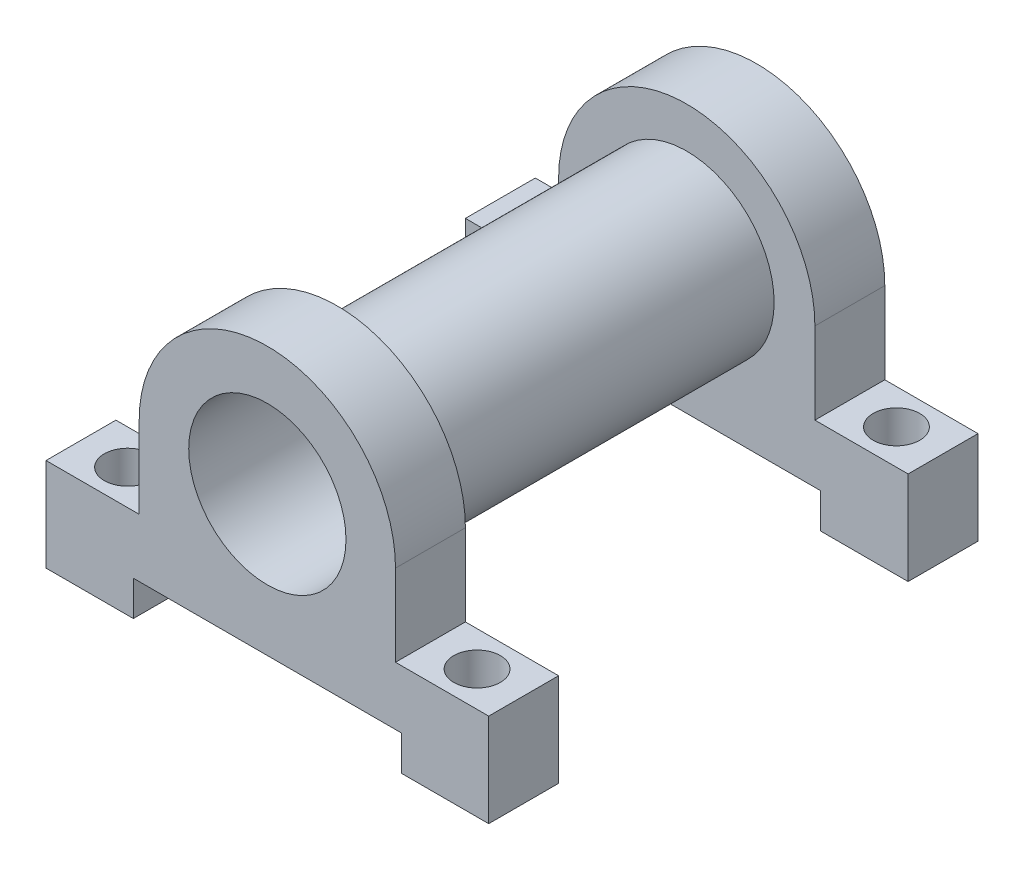
SolidWorks part; units mm, degrees
ref_plane "Front Plane" through (0, 0, 0) normal (0, 0, 1) x (1, 0, 0)
ref_plane "Top Plane" through (0, 0, 0) normal (0, 1, 0) x (1, 0, 0)
ref_plane "Right Plane" through (0, 0, 0) normal (1, 0, 0) x (0, 0, -1)
sketch "Sketch1" plane through (0, 0, 0) normal (0, 0, 1) x (1, 0, 0)
  line L0 (-11, 0) -> (-11, -7)
  line L1 (-11, -15) -> (11, -15)
  line L2 (11, -7) -> (11, 0)
  line L3 (-11, -7) -> (11, -7) construction
  line L4 (-11, -15) -> (-19, -15)
  line L6 (-11, -7) -> (-19, -7)
  line L7 (-19, -15) -> (-19, -7)
  line L8 (11, -15) -> (19, -15)
  line L10 (11, -7) -> (19, -7)
  line L11 (19, -15) -> (19, -7)
  line L12 (-11, 0) -> (11, 0) construction
  line L13 (-11, -7) -> (-11, -15) construction
  line L14 (11, -7) -> (11, -15) construction
  arc A0 (11, 0) -> (-11, 0) centre (0, 0) ccw
  dimension "D1" = 22
  dimension "D2" = 15
  dimension "D3" = 8
  dimension "D4" = 8
extrude "Boss-Extrude1" add sketch "Sketch1" along normal blind 6
sketch "Sketch2" plane through (0, 0, 6) normal (0, 0, 1) x (1, 0, 0)
  circle A0 centre (0, 0) radius 7.5
  dimension "D1" = 15
extrude "Boss-Extrude2" add sketch "Sketch2" along normal blind 30
sketch "Sketch3" plane through (0, 0, 36) normal (0, 0, 1) x (1, 0, 0)
  line L3 (-11, 0) -> (-11, -7)
  line L4 (-19, -15) -> (19, -15)
  line L5 (11, -7) -> (11, 0)
  line L6 (-11, 0) -> (-11, -7)
  line L7 (-19, -15) -> (19, -15)
  line L8 (11, -7) -> (11, 0)
  line L13 (-19, -7) -> (-19, -15)
  line L14 (-19, -7) -> (-19, -15)
  line L15 (19, -15) -> (19, -7)
  line L16 (19, -15) -> (19, -7)
  line L17 (19, -7) -> (11, -7)
  line L18 (19, -7) -> (11, -7)
  line L19 (-11, -7) -> (-19, -7)
  line L20 (-11, -7) -> (-19, -7)
  arc A2 (11, 0) -> (-11, 0) centre (0, 0) ccw
  arc A3 (11, 0) -> (-11, 0) centre (0, 0) ccw
  dimension "D1" = 0
extrude "Boss-Extrude3" add sketch "Sketch3" along normal blind 6
sketch "Sketch4" plane through (0, 0, 42) normal (0, 0, 1) x (1, 0, 0)
  circle A0 centre (0, 0) radius 6.75
  dimension "D1" = 13.5
extrude "Cut-Extrude1" cut sketch "Sketch4" against normal through all
sketch "Sketch5" plane through (0, 0, 0) normal (0, 0, -1) x (-1, 0, 0)
  line L0 (19, -15) -> (-19, -15) construction
  line L1 (-11.5, -15) -> (11.5, -15)
  line L2 (-11.5, -15) -> (-11.5, -12)
  line L3 (-11.5, -12) -> (11.5, -12)
  line L4 (11.5, -15) -> (11.5, -12)
  line L5 (0, -12) -> (0, 0) construction
  dimension "D1" = 23
  dimension "D2" = 3
extrude "Cut-Extrude2" cut sketch "Sketch5" against normal through all and the other way through all
sketch "Sketch6" plane through (0, -7, 0) normal (0, 1, 0) x (1, 0, 0)
  line L0 (-15, -3) -> (15, -3) construction
  line L1 (19, -42) -> (11, -42) construction
  line L3 (0, -3) -> (0, 0) construction
  circle A0 centre (-15, -3) radius 2
  circle A1 centre (15, -3) radius 2
  circle A2 centre (15, -39) radius 2
  circle A3 centre (-15, -39) radius 2
  dimension "D3" = 4
  dimension "D1" = 30
  dimension "D2" = 3
  dimension "D5" = 3
  dimension "D4" = 2
extrude "Cut-Extrude3" cut sketch "Sketch6" against normal through all
